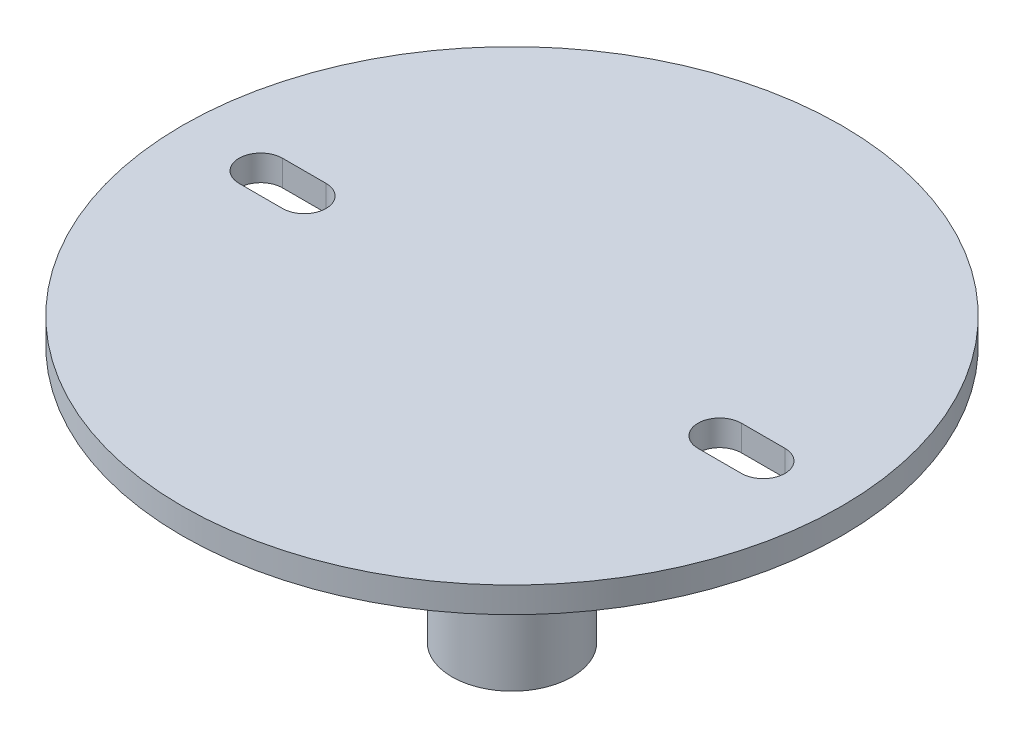
SolidWorks part; units mm, degrees
material "1060 Alloy"
ref_plane "Front" through (0, 0, 0) normal (0, 0, 1) x (1, 0, 0)
ref_plane "Top" through (0, 0, 0) normal (0, 1, 0) x (1, 0, 0)
ref_plane "Right" through (0, 0, 0) normal (1, 0, 0) x (0, 0, -1)
sketch "Sketch1" plane through (0, 0, 0) normal (0, 1, 0) x (1, 0, 0)
  line L0 (6.35, 0) -> (-6.35, 0) construction
  line L1 (14.66, 1.27) -> (12.12, 1.27)
  line L2 (14.66, -1.27) -> (12.12, -1.27)
  line L3 (0, 19.24) -> (0, -19.24) construction
  line L4 (-14.66, -1.27) -> (-12.12, -1.27)
  line L5 (-14.66, 1.27) -> (-12.12, 1.27)
  circle A0 centre (0, 0) radius 19.24
  arc A1 (12.12, 1.27) -> (12.12, -1.27) centre (12.12, 0) ccw
  arc A2 (14.66, 1.27) -> (14.66, -1.27) centre (14.66, 0) cw
  arc A3 (-14.66, 1.27) -> (-14.66, -1.27) centre (-14.66, 0) ccw
  arc A4 (-12.12, 1.27) -> (-12.12, -1.27) centre (-12.12, 0) cw
  point P5 (6.35, 0)
  point P12 (10.85, 0)
  point P21 (-10.85, 0)
  dimension "D1" = 38.48
  dimension "D3" = 1.27
  dimension "D2" = 2.54
  dimension "D7" = 10.85
extrude "Boss-Extrude1" add sketch "Sketch1" along normal blind 1.5
ref_plane "Plane1" through (0, 0, 0) normal (0, -1, 0) x (-1, 0, 0)
sketch "Sketch2" plane through (0, 0, 0) normal (0, -1, 0) x (-1, 0, 0)
  circle A0 centre (0, 0) radius 3.5
  circle A1 centre (0, 0) radius 2
  dimension "D1" = 7
  dimension "D2" = 4
extrude "Boss-Extrude2" add sketch "Sketch2" along normal blind 15
fillet "Fillet1" radius 1 1 edges at (0, 0, 3.5)
